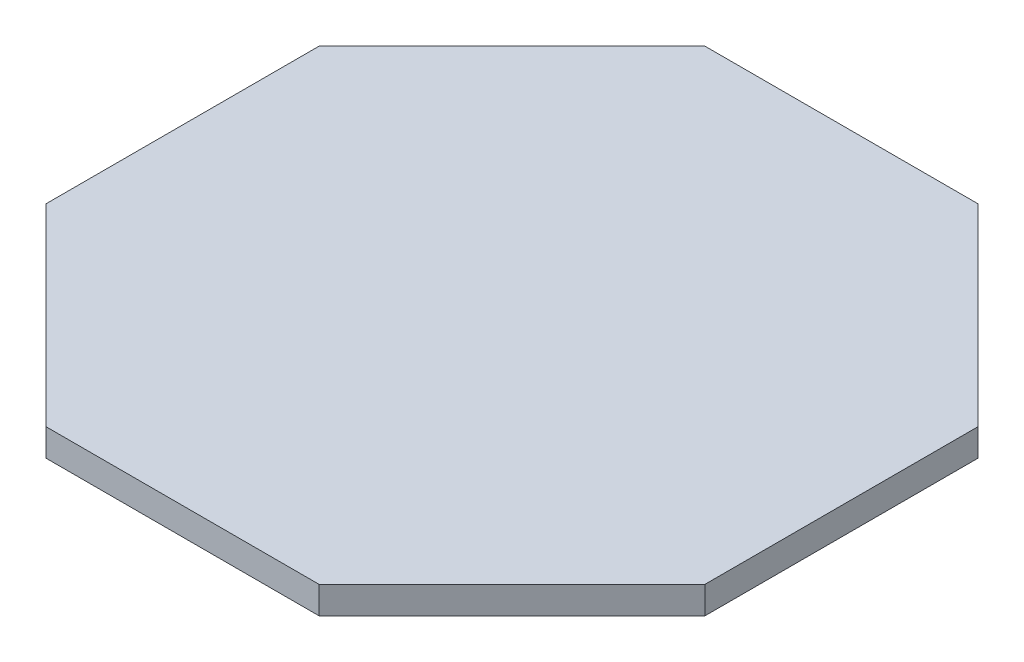
SolidWorks part; units mm, degrees
ref_plane "Front Plane" through (0, 0, 0) normal (0, 0, 1) x (1, 0, 0)
ref_plane "Top Plane" through (0, 0, 0) normal (0, 1, 0) x (1, 0, 0)
ref_plane "Right Plane" through (0, 0, 0) normal (1, 0, 0) x (0, 0, -1)
sketch "Sketch1" plane through (0, 0, 0) normal (0, 1, 0) x (1, 0, 0)
  line L1 (24.1421, 10) -> (10, 24.1421)
  line L2 (10, 24.1421) -> (-10, 24.1421)
  line L3 (-10, 24.1421) -> (-24.1421, 10)
  line L4 (-24.1421, 10) -> (-24.1421, -10)
  line L5 (-24.1421, -10) -> (-10, -24.1421)
  line L6 (-10, -24.1421) -> (10, -24.1421)
  line L7 (10, -24.1421) -> (24.1421, -10)
  line L8 (24.1421, -10) -> (24.1421, 10)
  circle A0 centre (0, 0) radius 24.1421 construction
  point P1 (0, 0)
  point P12 (-1.0152, 2.4078)
  dimension "D1" = 20
extrude "Boss-Extrude1" add sketch "Sketch1" along normal blind 2
